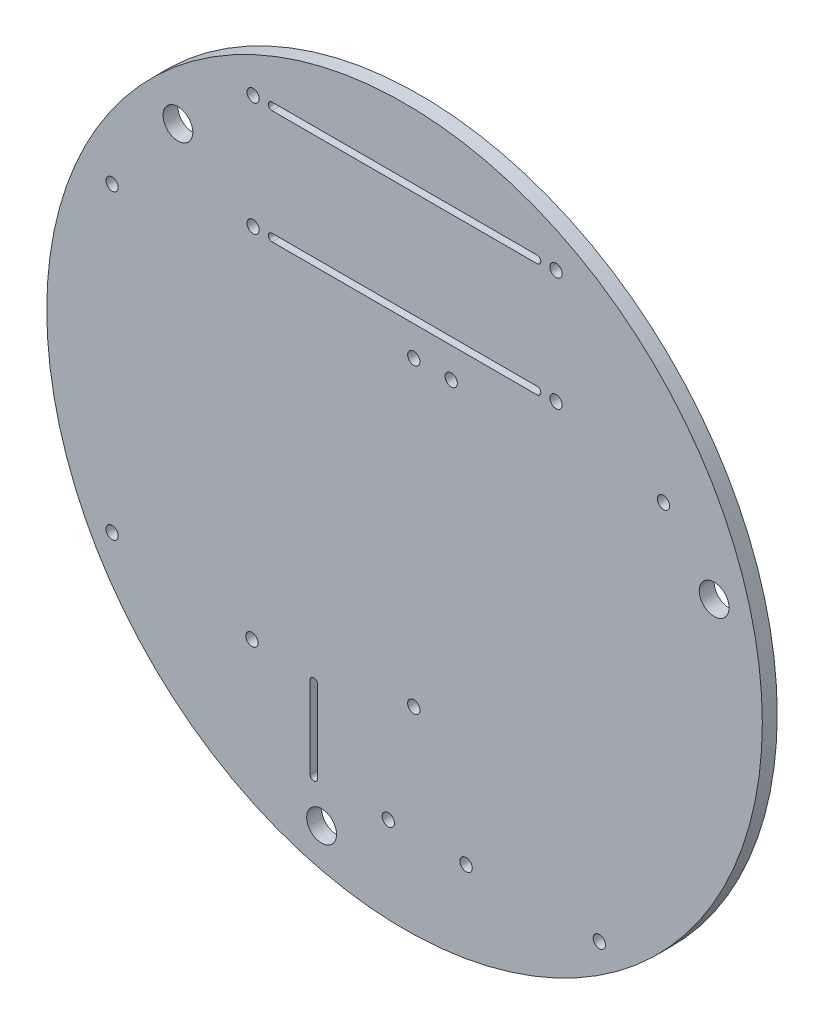
SolidWorks part; units mm, degrees
ref_plane "Plan de face" through (0, 0, 0) normal (0, 0, 1) x (1, 0, 0)
ref_plane "Plan de dessus" through (0, 0, 0) normal (0, 1, 0) x (1, 0, 0)
ref_plane "Plan de droite" through (0, 0, 0) normal (1, 0, 0) x (0, 0, -1)
sketch "Sketch1" plane through (0, 0, 0) normal (0, 0, 1) x (1, 0, 0)
  circle A0 centre (0, 0) radius 48
  dimension "D1" = 96
extrude "Boss-Extrude1" add sketch "Sketch1" along normal blind 2
sketch "Sketch3" plane through (0, 0, 0) normal (0, 0, -1) x (-1, 0, 0)
  line L0 (0, 0) -> (0, 43) construction
  line L1 (0, 0) -> (30.4056, 30.4056) construction
  circle A0 centre (0, 0) radius 43 construction
  circle A1 centre (30.4056, 30.4056) radius 2
  circle A2 centre (11.1292, -41.5348) radius 2
  circle A3 centre (-41.5348, 11.1292) radius 2
  point P13 (0, 0)
  dimension "D1" = 86
  dimension "D2" = 4
  dimension "D3" = 45
  dimension "D4" = 3
extrude "Cut-Extrude1" cut sketch "Sketch3" against normal through all contours A3 | A1 | A2
sketch "Sketch2" plane through (0, 0, 2) normal (0, 0, 1) x (1, 0, 0)
  line L0 (0, 40) -> (0, 22.24) construction
  line L1 (-21.58, 40) -> (21.58, 40) construction
  line L2 (-21.58, 40) -> (-21.58, 22.24) construction
  line L3 (-21.58, 22.24) -> (21.58, 22.24) construction
  line L4 (21.58, 40) -> (21.58, 22.24) construction
  line L5 (-21.58, 31.12) -> (21.58, 31.12) construction
  line L6 (20.5, 20.24) -> (20.5, -27.76) construction
  line L7 (5, 20.24) -> (36, 20.24) construction
  line L8 (5, 20.24) -> (5, -27.76) construction
  line L9 (5, -27.76) -> (36, -27.76) construction
  line L10 (36, 20.24) -> (36, -27.76) construction
  line L11 (-19, 20.24) -> (-19, -22.76) construction
  line L12 (-40.5, -22.76) -> (2.5, -22.76) construction
  line L13 (-40.5, -22.76) -> (-40.5, 20.24) construction
  line L14 (-40.5, 20.24) -> (2.5, 20.24) construction
  line L15 (2.5, -22.76) -> (2.5, 20.24) construction
  line L16 (-40.5, -1.26) -> (2.5, -1.26) construction
  line L17 (17.78, 23.5) -> (-17.78, 23.5) construction
  line L18 (17.78, 23) -> (-17.78, 23)
  line L19 (17.78, 24) -> (-17.78, 24)
  line L20 (17.78, 38.74) -> (-17.78, 38.74) construction
  line L21 (17.78, 39.24) -> (-17.78, 39.24)
  line L22 (17.78, 38.24) -> (-17.78, 38.24)
  circle A0 centre (20.32, 38.74) radius 0.825
  circle A1 centre (20.32, 23.5) radius 0.825
  circle A2 centre (-20.32, 23.5) radius 0.825
  circle A3 centre (-20.32, 38.74) radius 0.825
  circle A4 centre (34.74, 18.98) radius 0.825
  circle A5 centre (6.26, 18.98) radius 0.825
  circle A6 centre (-39.24, 18.98) radius 0.825
  circle A7 centre (1.24, 18.98) radius 0.825
  circle A8 centre (1.24, -21.5) radius 0.825
  circle A9 centre (-39.24, -21.5) radius 0.825
  arc A10 (17.78, 23) -> (17.78, 24) centre (17.78, 23.5) ccw
  arc A11 (-17.78, 24) -> (-17.78, 23) centre (-17.78, 23.5) ccw
  arc A12 (17.78, 39.24) -> (17.78, 38.24) centre (17.78, 38.74) cw
  arc A13 (-17.78, 38.24) -> (-17.78, 39.24) centre (-17.78, 38.74) cw
  point P9 (0, 31.12)
  point P46 (0, 23.5)
  point P55 (0, 38.74)
  dimension "D4" = 1.26
  dimension "D6" = 1.65
  dimension "D11" = 1.26
  dimension "D13" = 1.65
  dimension "D18" = 1.26
  dimension "D19" = 1.65
  dimension "D1" = 43.16
  dimension "D2" = 17.76
  dimension "D3" = 40
  dimension "D5" = 1.26
  dimension "D7" = 48
  dimension "D8" = 31
  dimension "D9" = 50
  dimension "D10" = 5
  dimension "D12" = 1.26
  dimension "D14" = 43
  dimension "D15" = 43
  dimension "D16" = 2.5
  dimension "D17" = 2
  dimension "D20" = 1
  dimension "D21" = 2.54
  dimension "D22" = 2.54
extrude "Cut-Extrude-Nano+Recto" cut sketch "Sketch2" against normal through all
sketch "Sketch4" plane through (0, 0, 0) normal (0, 0, -1) x (-1, 0, 0)
  line L0 (-27.39, -37.6) -> (-27.39, -22) construction
  line L1 (-27.39, -22) -> (-7, -22) construction
  line L2 (-7, -22) -> (-7, -37.6) construction
  line L3 (-7, -37.6) -> (-27.39, -37.6) construction
  line L4 (3.44, -37.6) -> (3.44, -24.56) construction
  line L5 (3.44, -24.56) -> (-7, -24.56) construction
  line L7 (-7, -37.6) -> (3.44, -37.6) construction
  line L8 (-17.195, -22) -> (-17.195, -37.6) construction
  line L9 (12.18, -36.34) -> (12.18, -25.34) construction
  line L12 (11.68, -36.34) -> (11.68, -25.34)
  line L13 (12.68, -36.34) -> (12.68, -25.34)
  circle A0 centre (-8.26, -36.34) radius 0.825
  circle A1 centre (2.18, -36.34) radius 0.825
  circle A2 centre (-26.13, -36.34) radius 0.825
  arc A7 (11.68, -36.34) -> (12.68, -36.34) centre (12.18, -36.34) ccw
  arc A8 (12.68, -25.34) -> (11.68, -25.34) centre (12.18, -25.34) ccw
  circle A9 centre (20.48, -24.54) radius 0.825
  point P18 (12.18, -30.84)
  dimension "D7" = 1.26
  dimension "D11" = 1.65
  dimension "D12" = 1.65
  dimension "D13" = 11
  dimension "D14" = 0.5
  dimension "D16" = 0.8
  dimension "D18" = 1.65
  dimension "D1" = 20.39
  dimension "D2" = 15.6
  dimension "D3" = 13.04
  dimension "D4" = 10.44
  dimension "D5" = 7
  dimension "D6" = 22
  dimension "D8" = 1.26
  dimension "D9" = 1.26
  dimension "D10" = 1.26
  dimension "D15" = 10
  dimension "D17" = 8.3
extrude "Cut-Extrude-Verso" cut sketch "Sketch4" against normal through all
